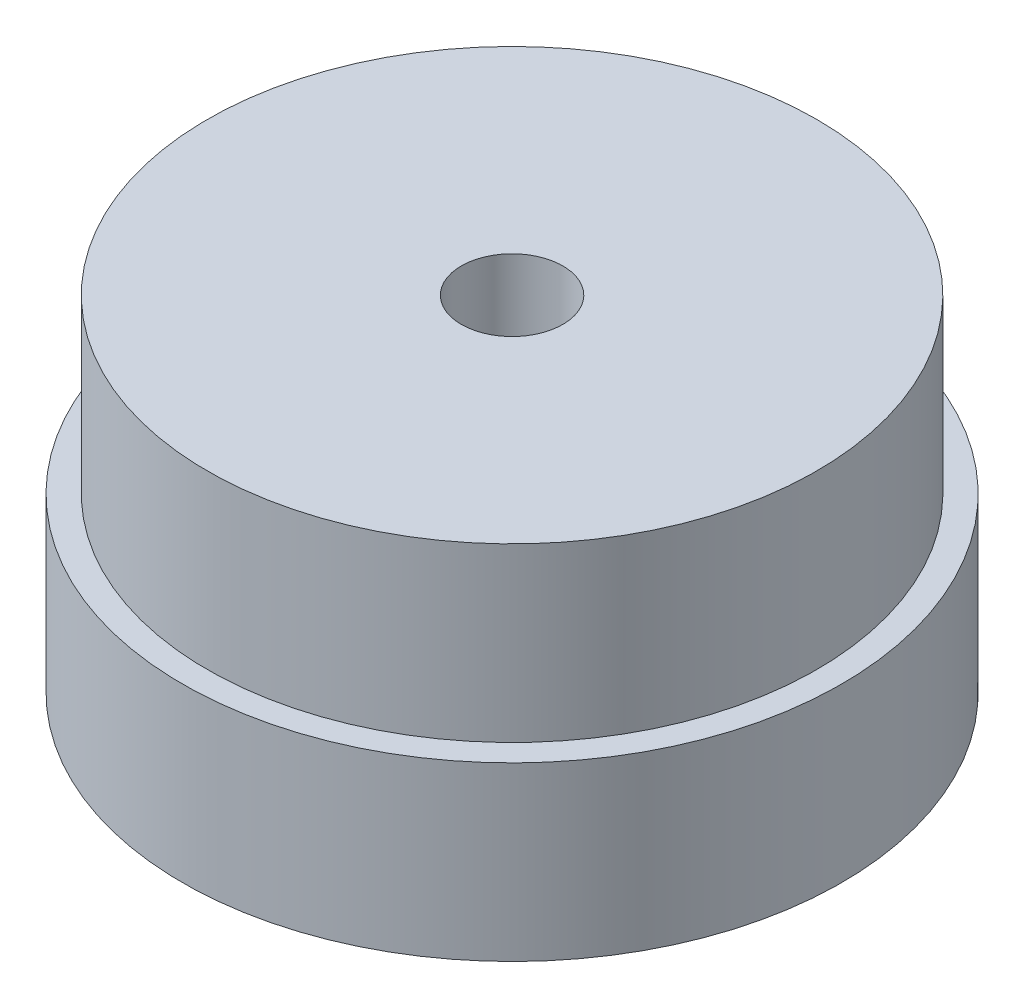
SolidWorks part; units mm, degrees
ref_plane "Front Plane" through (0, 0, 0) normal (0, 0, 1) x (1, 0, 0)
ref_plane "Top Plane" through (0, 0, 0) normal (0, 1, 0) x (1, 0, 0)
ref_plane "Right Plane" through (0, 0, 0) normal (1, 0, 0) x (0, 0, -1)
sketch "Sketch1" plane through (0, 0, 0) normal (0, 0, 1) x (1, 0, 0)
  line L0 (0, 0) -> (0, 17.2248)
  line L1 (0, 17.2248) -> (15.25, 17.2248)
  line L2 (15.25, 17.2248) -> (15.25, 8.6124)
  line L3 (15.25, 8.6124) -> (16.5, 8.6124)
  line L4 (16.5, 8.6124) -> (16.5, 0)
  line L5 (16.5, 0) -> (0, 0)
  dimension "D1" = 17.2248
  dimension "D2" = 8.6124
  dimension "D3" = 16.5
  dimension "D4" = 15.25
revolve "Revolve1" add sketch "Sketch1" angle 360 about L0
sketch "Sketch2" plane through (0, 17.2248, 0) normal (0, 1, 0) x (1, 0, 0)
  circle A0 centre (0, 0) radius 2.54
  dimension "D1" = 5.08
extrude "Cut-Extrude1" cut sketch "Sketch2" against normal through all contours A0
shell "Shell2" thickness 0.254
